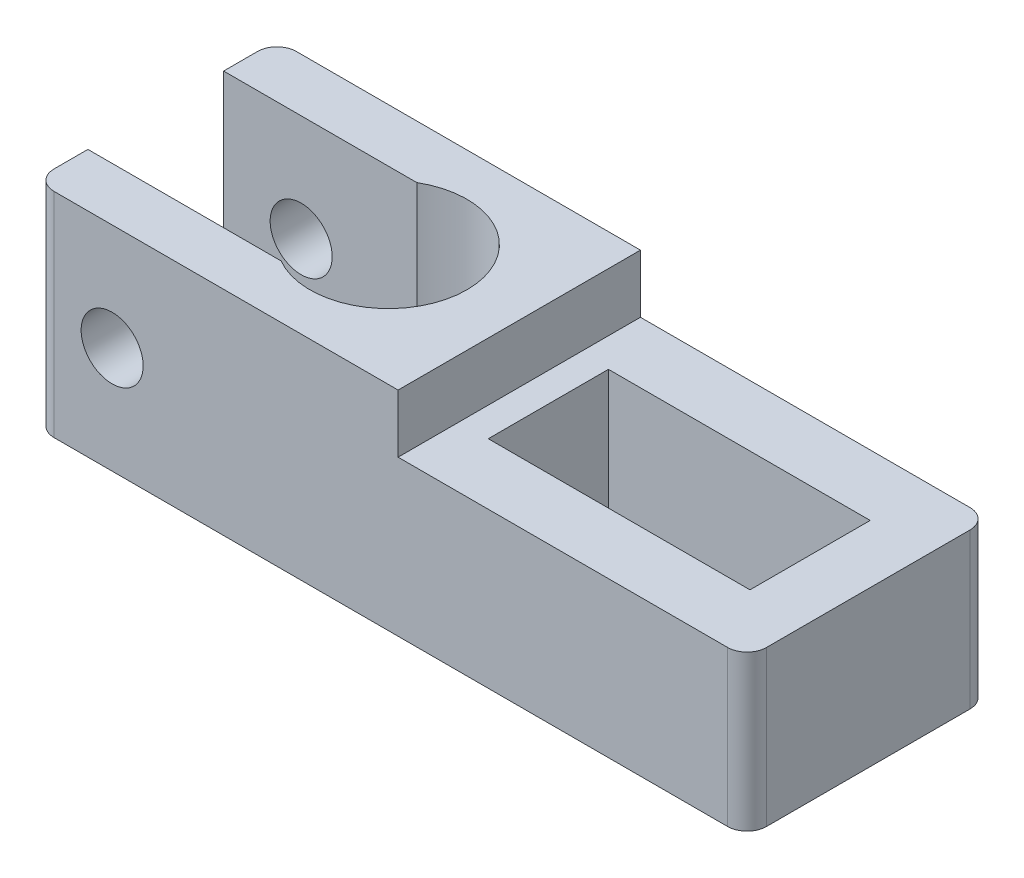
SolidWorks part; units mm, degrees
ref_plane "Front Plane" through (0, 0, 0) normal (0, 0, 1) x (1, 0, 0)
ref_plane "Top Plane" through (0, 0, 0) normal (0, 1, 0) x (1, 0, 0)
ref_plane "Right Plane" through (0, 0, 0) normal (1, 0, 0) x (0, 0, -1)
sketch "Sketch1" plane through (0, 0, 0) normal (0, 1, 0) x (1, 0, 0)
  line L0 (-10.5189, 0) -> (54.1167, 0) construction
  line L2 (21.75, -3.1) -> (8.25, -3.1)
  line L3 (21.75, -3.1) -> (21.75, 3.1)
  line L4 (21.75, 3.1) -> (8.25, 3.1)
  line L5 (8.25, -3.1) -> (8.25, 3.1)
  line L6 (21.75, -3.1) -> (8.25, 3.1) construction
  line L7 (21.75, 3.1) -> (8.25, -3.1) construction
  line L8 (24.75, -6.25) -> (-12, -6.25)
  line L9 (24.75, -6.25) -> (24.75, 6.25)
  line L10 (24.75, 6.25) -> (-12, 6.25)
  line L11 (-12, -6.25) -> (-12, 6.25)
  line L12 (24.75, -6.25) -> (-12, 6.25) construction
  line L13 (24.75, 6.25) -> (-12, -6.25) construction
  line L14 (-1, -3.5) -> (-12, -3.5)
  line L15 (-1, -3.5) -> (-1, 3.5)
  line L16 (-1, 3.5) -> (-12, 3.5)
  line L17 (-12, -3.5) -> (-12, 3.5)
  line L18 (-1, -3.5) -> (-12, 3.5) construction
  line L19 (-1, 3.5) -> (-12, -3.5) construction
  circle A0 centre (0, 0) radius 4.05
  point P5 (15, 0)
  point P10 (6.375, 0)
  point P15 (-6.5, 0)
  dimension "D1" = 8.1
  dimension "D2" = 6.2
  dimension "D3" = 13.5
  dimension "D4" = 15
  dimension "D5" = 3
  dimension "D6" = 12.5
  dimension "D7" = 12
  dimension "D8" = 7
  dimension "D9" = 11
extrude "Boss-Extrude1" add sketch "Sketch1" along normal blind 11 contours A0 L14 L11 L8 L9 L10 L16 L2 L5 L4 L3
sketch "Sketch2" plane through (0, 0, 6.25) normal (0, 0, 1) x (1, 0, 0)
  line L0 (-12, 5.5) -> (5.9698, 5.5) construction
  line L1 (-12, 11) -> (-12, 0) construction
  line L2 (24.75, 0) -> (-12, 0) construction
  circle A0 centre (-8, 5.5) radius 1.6
  point P6 (0, 0)
  dimension "D1" = 3.2
  dimension "D2" = 4
  dimension "D3" = 5.5
extrude "Cut-Extrude1" cut sketch "Sketch2" against normal through all
fillet "Fillet1" radius 1 4 edges at (-12, 5.5, 6.25) (-12, 5.5, -6.25) (24.75, 5.5, 6.25) (24.75, 5.5, -6.25)
sketch "Sketch3" plane through (0, 0, 6.25) normal (0, 0, 1) x (1, 0, 0)
  line L0 (23.75, 0) -> (-11, 0) construction
  line L1 (24.75, 11) -> (6.75, 11)
  line L2 (24.75, 11) -> (24.75, 8)
  line L3 (24.75, 8) -> (6.75, 8)
  line L4 (6.75, 11) -> (6.75, 8)
  dimension "D1" = 8
  dimension "D2" = 18
extrude "Cut-Extrude2" cut sketch "Sketch3" against normal through all
